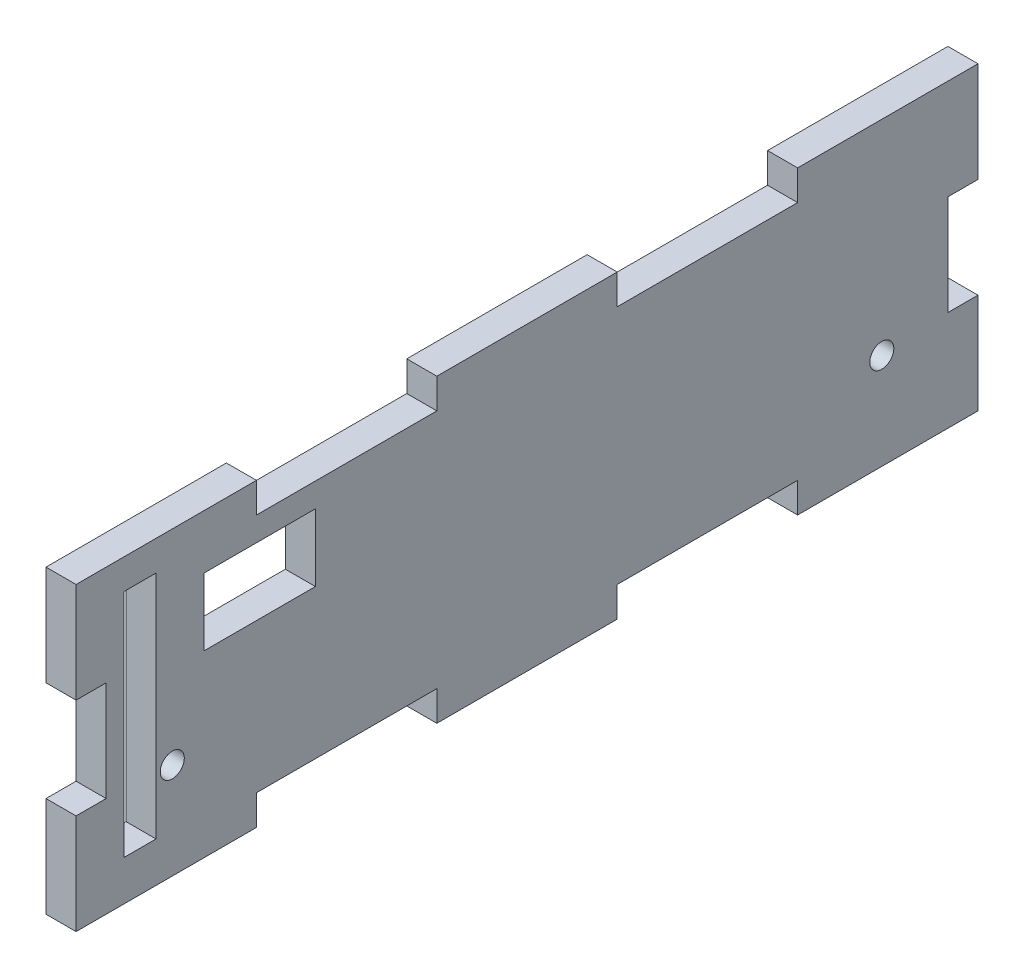
SolidWorks part; units mm, degrees
ref_plane "Alzado" through (0, 0, 0) normal (0, 0, 1) x (1, 0, 0)
ref_plane "Planta" through (0, 0, 0) normal (0, 1, 0) x (1, 0, 0)
ref_plane "Vista lateral" through (0, 0, 0) normal (1, 0, 0) x (0, 0, -1)
sketch "Croquis1" plane through (0, 0, 0) normal (1, 0, 0) x (0, 0, -1)
  line L0 (0, 33.3333) -> (5, 33.3333)
  line L1 (0, 0) -> (30, 0)
  line L2 (0, 0) -> (0, 16.6667)
  line L3 (0, 50) -> (30, 50)
  line L4 (150, 0) -> (150, 16.6667)
  line L5 (5, 33.3333) -> (5, 16.6667)
  line L6 (5, 16.6667) -> (0, 16.6667)
  line L7 (75, 40) -> (75, 31.2401) construction
  line L8 (145, 16.6667) -> (150, 16.6667)
  line L9 (145, 33.3333) -> (145, 16.6667)
  line L10 (150, 33.3333) -> (145, 33.3333)
  line L11 (30, 0) -> (30, 5)
  line L12 (30, 5) -> (60, 5)
  line L13 (60, 5) -> (60, 0)
  line L14 (120, 0) -> (120, 5)
  line L15 (90, 5) -> (90, 0)
  line L16 (120, 5) -> (90, 5)
  line L17 (5, 25) -> (8.4564, 25) construction
  line L18 (120, 50) -> (120, 45)
  line L19 (120, 45) -> (90, 45)
  line L20 (90, 45) -> (90, 50)
  line L21 (60, 45) -> (60, 50)
  line L22 (30, 50) -> (30, 45)
  line L23 (30, 45) -> (60, 45)
  line L24 (0, 33.3333) -> (0, 50)
  line L25 (60, 50) -> (90, 50)
  line L26 (60, 0) -> (90, 0)
  line L27 (120, 0) -> (150, 0)
  line L28 (120, 50) -> (150, 50)
  line L29 (150, 33.3333) -> (150, 50)
  circle A0 centre (16, 16) radius 2
  circle A1 centre (134, 16) radius 2
  dimension "D4" = 4
  dimension "D1" = 150
  dimension "D2" = 50
  dimension "D3" = 5
  dimension "D5" = 16.6667
  dimension "D6" = 30
  dimension "D7" = 30
  dimension "D8" = 5
  dimension "D9" = 16
  dimension "D10" = 16
extrude "Saliente-Extruir1" add sketch "Croquis1" along normal blind 5
sketch "Croquis2" plane through (5, 0, 0) normal (1, 0, 0) x (0, 0, -1)
  line L0 (5, 33.3333) -> (5, 16.6667) construction
  line L1 (8, 45) -> (13.3, 45)
  line L2 (8, 45) -> (8, 6.6965)
  line L3 (8, 6.6965) -> (13.3, 6.6965)
  line L4 (13.3, 45) -> (13.3, 6.6965)
  line L5 (60, 45) -> (30, 45) construction
  line L7 (21.3, 41) -> (39.8, 41)
  line L8 (21.3, 41) -> (21.3, 29.8)
  line L9 (21.3, 29.8) -> (39.8, 29.8)
  line L10 (39.8, 41) -> (39.8, 29.8)
  dimension "D1" = 5.3
  dimension "D2" = 3
  dimension "D3" = 18.5
  dimension "D4" = 11.2
  dimension "D5" = 4
  dimension "D6" = 8
extrude "Cortar-Extruir1" cut sketch "Croquis2" against normal blind 10
